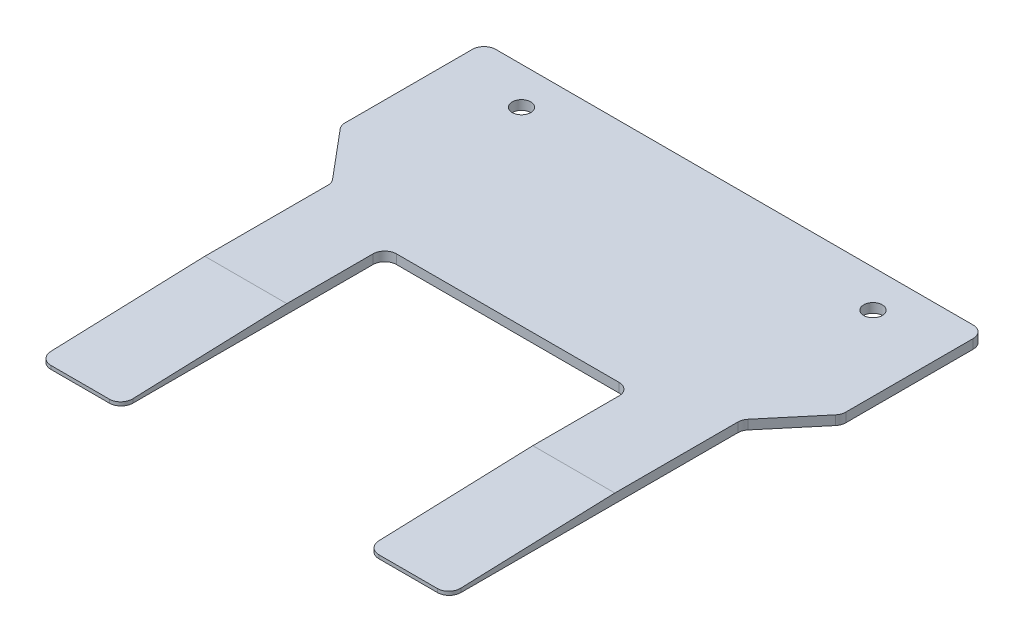
SolidWorks part; units mm, degrees
ref_plane "Front Plane" through (0, 0, 0) normal (0, 0, 1) x (1, 0, 0)
ref_plane "Top Plane" through (0, 0, 0) normal (0, 1, 0) x (1, 0, 0)
ref_plane "Right Plane" through (0, 0, 0) normal (1, 0, 0) x (0, 0, -1)
sketch "Sketch1" plane through (0, 0, 0) normal (0, 1, 0) x (1, 0, 0)
  line L0 (-35, -34.4279) -> (-35, -81.7)
  line L9 (-35.4679, -33.1424) -> (-42.2821, -25.0215)
  line L10 (-42.75, -23.736) -> (-42.75, -2)
  line L13 (42.75, -2) -> (42.75, -23.736)
  line L14 (42.2821, -25.0215) -> (35.4679, -33.1424)
  line L16 (-40.75, 0) -> (40.75, 0)
  line L17 (-33, -83.7) -> (-23, -83.7)
  line L18 (35, -81.7) -> (35, -34.4279)
  line L19 (-21, -81.7) -> (-21, -40.7)
  line L20 (-19, -38.7) -> (19, -38.7)
  line L21 (21, -40.7) -> (21, -81.7)
  line L22 (23, -83.7) -> (33, -83.7)
  line L23 (-42.75, -12.7) -> (42.75, -12.7) construction
  arc A8 (-21, -40.7) -> (-19, -38.7) centre (-19, -40.7) cw
  arc A9 (19, -38.7) -> (21, -40.7) centre (19, -40.7) cw
  arc A10 (33, -83.7) -> (35, -81.7) centre (33, -81.7) ccw
  arc A11 (21, -81.7) -> (23, -83.7) centre (23, -81.7) ccw
  arc A12 (-21, -81.7) -> (-23, -83.7) centre (-23, -81.7) cw
  arc A13 (-35, -81.7) -> (-33, -83.7) centre (-33, -81.7) ccw
  circle A14 centre (-30, -6.35) radius 1.5875
  circle A15 centre (30, -6.35) radius 1.5875
  arc A16 (35.4679, -33.1424) -> (35, -34.4279) centre (37, -34.4279) ccw
  arc A17 (42.75, -23.736) -> (42.2821, -25.0215) centre (40.75, -23.736) cw
  arc A18 (40.75, 0) -> (42.75, -2) centre (40.75, -2) cw
  arc A19 (-42.75, -2) -> (-40.75, 0) centre (-40.75, -2) cw
  arc A20 (-42.2821, -25.0215) -> (-42.75, -23.736) centre (-40.75, -23.736) cw
  arc A21 (-35.4679, -33.1424) -> (-35, -34.4279) centre (-37, -34.4279) cw
  point P8 (-21, -38.7)
  point P14 (35, 0)
  point P16 (21, -83.7)
  point P17 (-35, 0)
  point P20 (-21, -83.7)
  point P23 (-35, -83.7)
  point P30 (0, 0)
  point P33 (26.0899, -3.3115)
  point P34 (35, -33.7)
  point P39 (42.75, -24.4639)
  point P47 (42.75, 0)
  point P50 (-42.75, 0)
  point P53 (-42.75, -24.4639)
  point P56 (-35, -33.7)
  dimension "D7" = 50
  dimension "D8" = 140
  dimension "D9" = 2
  dimension "D13" = 3.175
  dimension "D15" = 2
  dimension "D1" = 83.7
  dimension "D2" = 42
  dimension "D3" = 85.5
  dimension "D4" = 45
  dimension "D5" = 14
  dimension "D6" = 70
  dimension "D10" = 12.7
  dimension "D11" = 60
  dimension "D12" = 12.75
  dimension "D14" = 6.35
extrude "Boss-Extrude1" add sketch "Sketch1" along normal blind 1.5875
ref_plane "Plane1" through (37, 0, 0) normal (1, 0, 0) x (0, 0, -1)
sketch "Sketch3" plane through (37, 0, 0) normal (1, 0, 0) x (0, 0, -1)
  line L0 (-81.7, 1.5875) -> (-34.4279, 1.5875) construction
  line L1 (-81.7, 1.5875) -> (-83.7, 1.5875) construction
  line L2 (-83.7, 1.5875) -> (-83.7, 0) construction
  line L3 (-81.7, 1.5875) -> (-55.4217, 1.5875)
  line L4 (-81.7, 1.5875) -> (-83.7, 1.5875)
  line L5 (-83.7, 1.5875) -> (-83.7, 0.6)
  line L6 (-83.7, 0.6) -> (-55.4217, 1.5875)
  line L7 (-83.7, 0) -> (-81.7, 0) construction
  point P6 (0, 0)
  point P9 (0, 0)
  dimension "D1" = 2
  dimension "D2" = 0.6
extrude "Cut-Extrude2" cut sketch "Sketch3" against normal through all
